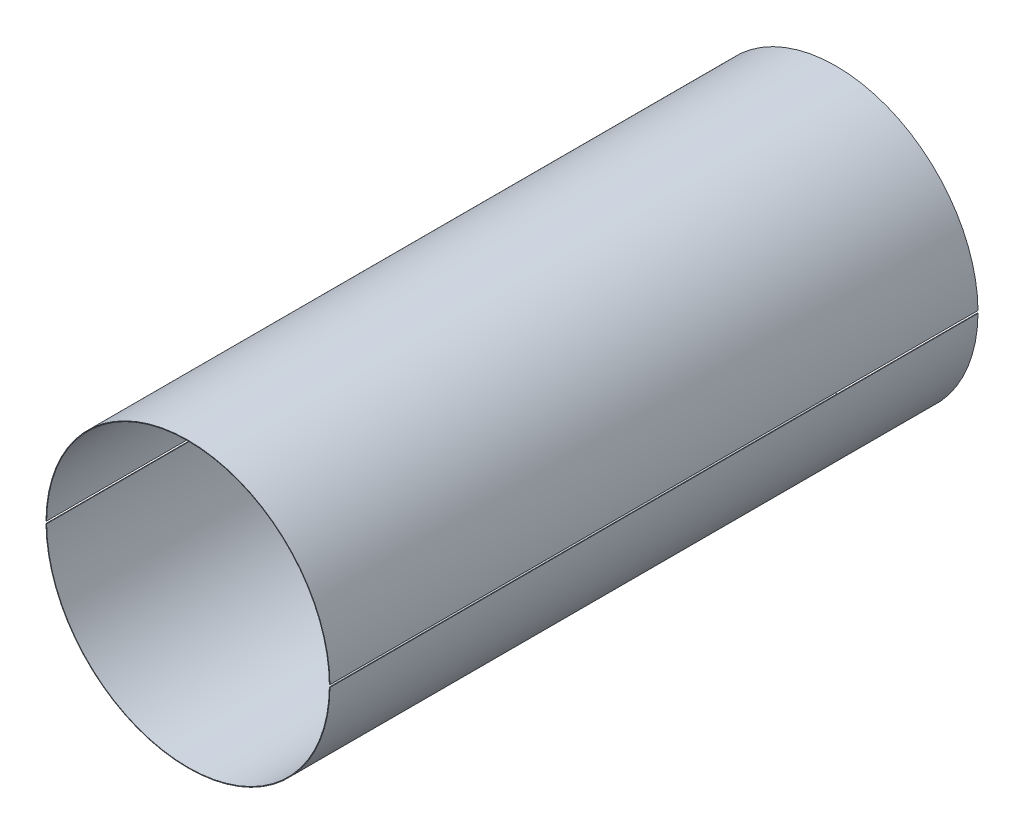
SolidWorks part; units mm, degrees
ref_plane "Front" through (0, 0, 0) normal (0, 0, 1) x (1, 0, 0)
ref_plane "Top" through (0, 0, 0) normal (0, 1, 0) x (1, 0, 0)
ref_plane "Right" through (0, 0, 0) normal (1, 0, 0) x (0, 0, -1)
sketch "Sketch2" plane through (0, 0, 0) normal (0, 0, 1) x (1, 0, 0)
  circle A0 centre (0, 0) radius 61.214
  circle A1 centre (0, 0) radius 60.96
  dimension "D1" = 122.428
  dimension "D2" = 121.92
extrude "Boss-Extrude1" add sketch "Sketch2" along normal blind 279.4
sketch "Sketch3" plane through (0, 0, 279.4) normal (0, 0, 1) x (1, 0, 0)
  line L0 (-71.4518, 0) -> (70.1682, 0) construction
  line L1 (0, 68.3498) -> (0, -67.2802) construction
ref_plane "Plane1" through (-61.214, 0, 0) normal (-1, 0, 0) x (0, 0, 1)
sketch "Sketch5" plane through (-61.214, 0, 0) normal (-1, 0, 0) x (0, 0, 1)
  line L0 (-8.3863, 0) -> (289.133, 0) construction
  line L1 (0, 0.508) -> (279.4, 0.508)
  line L2 (0, 61.214) -> (0, -61.214) construction
  line L3 (279.4, 68.3498) -> (279.4, -67.2802) construction
  line L4 (279.4, 0.508) -> (279.4, -0.508)
  line L5 (0, 0.508) -> (0, -0.508)
  line L6 (0, -0.508) -> (279.4, -0.508)
  point P12 (279.4, 0)
  point P13 (0, 0)
  dimension "D1" = 0.508
extrude "Cut-Extrude1" cut sketch "Sketch5" against normal through all both and the other way through all
